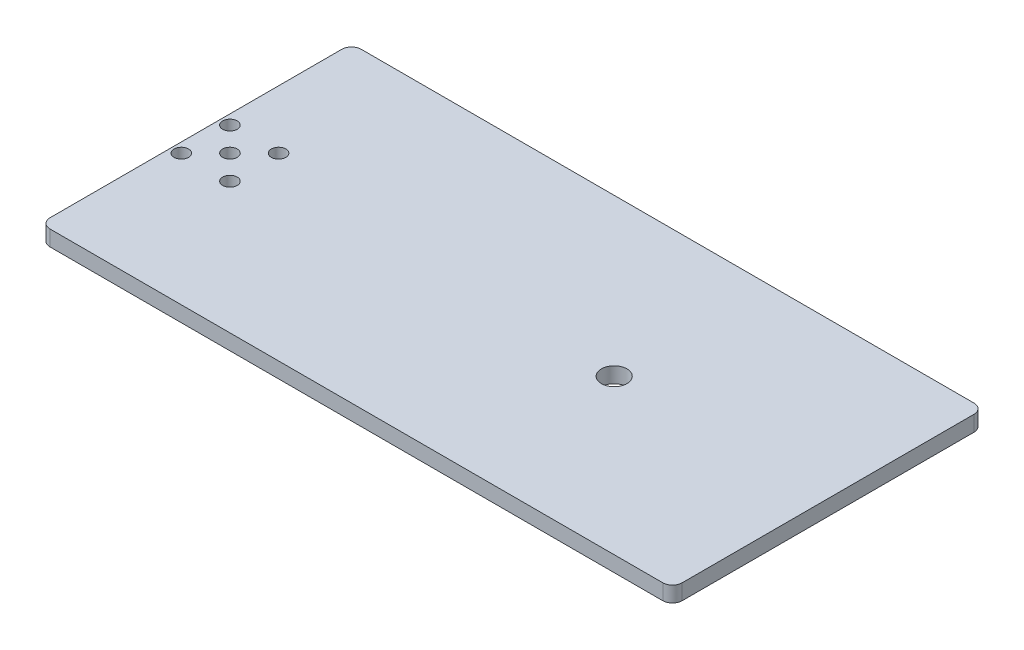
SolidWorks part; units mm, degrees
ref_plane "Front" through (0, 0, 0) normal (0, 0, 1) x (1, 0, 0)
ref_plane "Top" through (0, 0, 0) normal (0, 1, 0) x (1, 0, 0)
ref_plane "Right" through (0, 0, 0) normal (1, 0, 0) x (0, 0, -1)
sketch "Sketch1" plane through (0, 0, 0) normal (0, 1, 0) x (1, 0, 0)
  line L1 (1, 0) -> (64, 0)
  line L2 (0, 1) -> (0, 31)
  line L3 (1, 32) -> (64, 32)
  line L4 (65, 1) -> (65, 31)
  arc A0 (1, 0) -> (0, 1) centre (1, 1) cw
  arc A1 (64, 0) -> (65, 1) centre (64, 1) ccw
  arc A2 (64, 32) -> (65, 31) centre (64, 31) cw
  arc A3 (0, 31) -> (1, 32) centre (1, 31) cw
  point P7 (0, 0)
  point P10 (65, 0)
  point P13 (65, 32)
  point P16 (0, 32)
  dimension "D3" = 1
  dimension "D1" = 32
  dimension "D2" = 65
extrude "Boss-Extrude1" add sketch "Sketch1" along normal blind 1.6
sketch "Sketch4" plane through (65, 0, 0) normal (1, 0, 0) x (0, 0, -1)
  line L0 (1, 0) -> (31, 0) construction
  line L1 (7, 0) -> (25, 0)
  line L2 (6, 1) -> (6, 7)
  line L3 (7, 8) -> (25, 8)
  line L4 (26, 1) -> (26, 7)
  line L5 (1, 1.6) -> (31, 1.6) construction
  arc A0 (7, 0) -> (6, 1) centre (7, 1) cw
  arc A1 (25, 0) -> (26, 1) centre (25, 1) ccw
  arc A2 (25, 8) -> (26, 7) centre (25, 7) cw
  arc A3 (6, 7) -> (7, 8) centre (7, 7) cw
  point P6 (16, 1.6)
  point P11 (6, 0)
  point P14 (26, 0)
  point P17 (26, 8)
  point P20 (6, 8)
  dimension "D4" = 1
  dimension "D1" = 8
  dimension "D2" = 20
  dimension "D3" = 10
extrude "Boss-Extrude3" [suppressed] add sketch "Sketch4" along normal blind 2
sketch "Sketch5" [suppressed] plane through (0, 2, 0) normal (0, 1, 0) x (1, 0, 0)
  line L0 (46, 6) -> (46, 26) construction
  line L1 (46, 22) -> (44, 22)
  line L2 (46, 22) -> (46, 21.2889)
  line L3 (46, 21.2889) -> (44, 21.2889)
  line L4 (44, 22) -> (44, 21.2889)
  line L5 (46, 20) -> (46, 19.2889)
  line L6 (46, 20) -> (44, 20)
  line L7 (44, 20) -> (44, 19.2889)
  line L8 (46, 19.2889) -> (44, 19.2889)
  line L9 (46, 18) -> (46, 17.2889)
  line L10 (46, 18) -> (44, 18)
  line L11 (44, 18) -> (44, 17.2889)
  line L12 (46, 17.2889) -> (44, 17.2889)
  line L13 (46, 16) -> (46, 15.2889)
  line L14 (46, 16) -> (44, 16)
  line L15 (44, 16) -> (44, 15.2889)
  line L16 (46, 15.2889) -> (44, 15.2889)
  line L17 (46, 14) -> (46, 13.2889)
  line L18 (46, 14) -> (44, 14)
  line L19 (44, 14) -> (44, 13.2889)
  line L20 (46, 13.2889) -> (44, 13.2889)
  line L21 (46, 12) -> (46, 11.2889)
  line L22 (46, 12) -> (44, 12)
  line L23 (44, 12) -> (44, 11.2889)
  line L24 (46, 11.2889) -> (44, 11.2889)
  dimension "D2" = 2
  dimension "D3" = 4
  dimension "D1" = 6
extrude "Boss-Extrude4" [suppressed] add sketch "Sketch5" along normal blind 0.1
sketch "Sketch6" [suppressed] plane through (46, 0, 0) normal (-1, 0, 0) x (0, 0, 1)
  line L0 (-20, 2.1) -> (-20, 4.1)
  line L1 (-22, 2.1) -> (-21.2889, 2.1)
  line L2 (-22, 2.1) -> (-22, 4.1)
  line L3 (-22, 4.1) -> (-21.2889, 4.1)
  line L4 (-21.2889, 2.1) -> (-21.2889, 4.1)
  line L5 (-20, 4.1) -> (-19.2889, 4.1)
  line L6 (-19.2889, 2.1) -> (-19.2889, 4.1)
  line L7 (-20, 2.1) -> (-19.2889, 2.1)
  line L8 (-18, 2.1) -> (-18, 4.1)
  line L9 (-18, 4.1) -> (-17.2889, 4.1)
  line L10 (-17.2889, 2.1) -> (-17.2889, 4.1)
  line L11 (-18, 2.1) -> (-17.2889, 2.1)
  line L12 (-16, 2.1) -> (-16, 4.1)
  line L13 (-16, 4.1) -> (-15.2889, 4.1)
  line L14 (-15.2889, 2.1) -> (-15.2889, 4.1)
  line L15 (-16, 2.1) -> (-15.2889, 2.1)
  line L16 (-14, 2.1) -> (-14, 4.1)
  line L17 (-14, 4.1) -> (-13.2889, 4.1)
  line L18 (-13.2889, 2.1) -> (-13.2889, 4.1)
  line L19 (-14, 2.1) -> (-13.2889, 2.1)
  line L20 (-12, 2.1) -> (-12, 4.1)
  line L21 (-12, 4.1) -> (-11.2889, 4.1)
  line L22 (-11.2889, 2.1) -> (-11.2889, 4.1)
  line L23 (-12, 2.1) -> (-11.2889, 2.1)
  dimension "D1" = 2
  dimension "D2" = 6
extrude "Boss-Extrude5" [suppressed] add sketch "Sketch6" along normal blind 0.1
sketch "Sketch8" plane through (0, 1.6, 0) normal (0, 1, 0) x (1, 0, 0)
  line L0 (64, 32) -> (1, 32) construction
  line L1 (0, 31) -> (0, 1) construction
  circle A0 centre (3.5, 16) radius 0.75
  circle A1 centre (6, 18.5) radius 0.75
  circle A2 centre (6, 13.5) radius 0.75
  circle A3 centre (1, 13.5) radius 0.75
  circle A4 centre (1, 18.5) radius 0.75
  dimension "D1" = 1.5
  dimension "D2" = 1.5
  dimension "D3" = 1.5
  dimension "D4" = 1.5
  dimension "D5" = 1.5
  dimension "D6" = 5
  dimension "D7" = 5
  dimension "D8" = 5
  dimension "D9" = 5
  dimension "D10" = 2.5
  dimension "D11" = 2.5
  dimension "D12" = 16
  dimension "D13" = 3.5
extrude "Cut-Extrude2" cut sketch "Sketch8" against normal up to next
sketch "Sketch9" plane through (0, 1.6, 0) normal (0, 1, 0) x (1, 0, 0)
  circle A0 centre (43.115, 15.8909) radius 1.3165
extrude "Cut-Extrude3" cut sketch "Sketch9" against normal up to next
